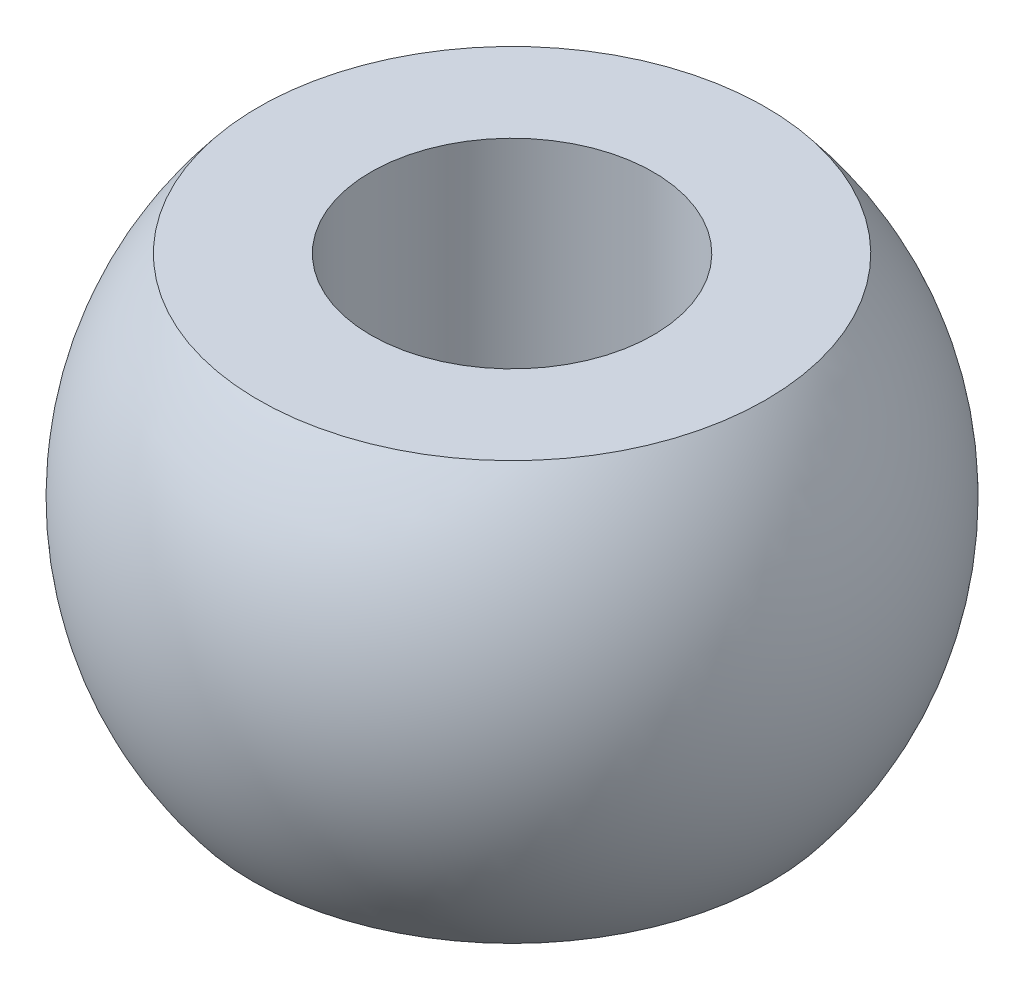
SolidWorks part; units mm, degrees
ref_plane "Front Plane" through (0, 0, 0) normal (0, 0, 1) x (1, 0, 0)
ref_plane "Top Plane" through (0, 0, 0) normal (0, 1, 0) x (1, 0, 0)
ref_plane "Right Plane" through (0, 0, 0) normal (1, 0, 0) x (0, 0, -1)
sketch "Sketch1" plane through (0, 0, 0) normal (0, 0, 1) x (1, 0, 0)
  line L0 (0, 2.941) -> (0, -3.5) construction
  line L1 (1.5, 2.2349) -> (1.5, -0.3651)
  line L2 (1.5, -0.3651) -> (2.25, -0.3651)
  line L3 (2.25, -0.3651) -> (2.25, -2.1651)
  line L4 (2.25, -2.1651) -> (2.75, -2.1651)
  line L5 (1.5, 2.2349) -> (2.6935, 2.2349)
  arc A0 (2.75, -2.1651) -> (2.6935, 2.2349) centre (0, 0) ccw
  dimension "D1" = 3.5
  dimension "D2" = 4.4
  dimension "D3" = 3
  dimension "D4" = 4.5
  dimension "D5" = 1.8
  dimension "D6" = 0.5
revolve "Revolve1" add sketch "Sketch1" angle 360 about L0
